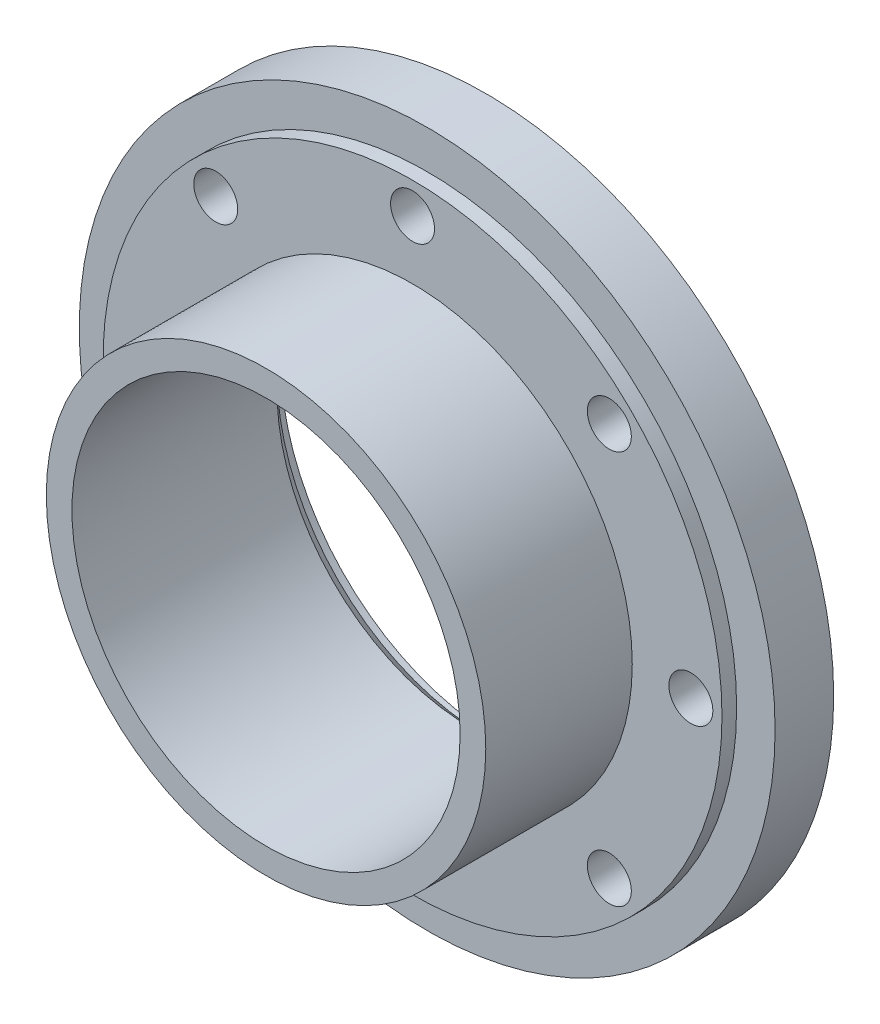
SolidWorks part; units mm, degrees
ref_plane "前视基准面" through (0, 0, 0) normal (0, 0, 1) x (1, 0, 0)
ref_plane "上视基准面" through (0, 0, 0) normal (0, 1, 0) x (1, 0, 0)
ref_plane "右视基准面" through (0, 0, 0) normal (1, 0, 0) x (0, 0, -1)
sketch "草图1" plane through (0, 0, 0) normal (0, 0, 1) x (1, 0, 0)
  circle A0 centre (0, 0) radius 47.5
  dimension "D1" = 95
extrude "拉伸1" add sketch "草图1" along normal blind 10
sketch "草图2" plane through (0, 0, 10) normal (0, 0, 1) x (1, 0, 0)
  circle A0 centre (0, 0) radius 30
  dimension "D1" = 60
extrude "拉伸2" add sketch "草图2" along normal blind 20
sketch "草图3" plane through (0, 0, 30) normal (0, 0, 1) x (1, 0, 0)
  circle A0 centre (0, 0) radius 26.5
  dimension "D1" = 53
extrude "切除-拉伸1" cut sketch "草图3" against normal blind 40
sketch "草图4" plane through (0, 0, 0) normal (0, 0, -1) x (-1, 0, 0)
  circle A0 centre (0, 0) radius 34
  circle A1 centre (0, 0) radius 30
  dimension "D1" = 60
  dimension "D2" = 68
extrude "拉伸3" add sketch "草图4" along normal blind 2
sketch "草图5" plane through (0, 0, 10) normal (0, 0, 1) x (1, 0, 0)
  circle A0 centre (0, 0) radius 42.25
  circle A1 centre (0, 0) radius 47.5
  dimension "D1" = 84.5
extrude "切除-拉伸2" cut sketch "草图5" against normal blind 2
sketch "草图6" plane through (0, 0, 10) normal (0, 0, 1) x (1, 0, 0)
  circle A0 centre (26.8701, 26.8701) radius 3
  circle A1 centre (0, 38) radius 3
  circle A2 centre (38, 0) radius 3
  circle A3 centre (26.8701, -26.8701) radius 3
  circle A4 centre (0, -38) radius 3
  circle A5 centre (-26.8701, -26.8701) radius 3
  circle A6 centre (-38, 0) radius 3
  circle A7 centre (-26.8701, 26.8701) radius 3
  dimension "D1" = 6
extrude "切除-拉伸3" cut sketch "草图6" against normal blind 10
chamfer "倒角1" distance 2 angle 45 1 edges at (26.5, 0, 0)
